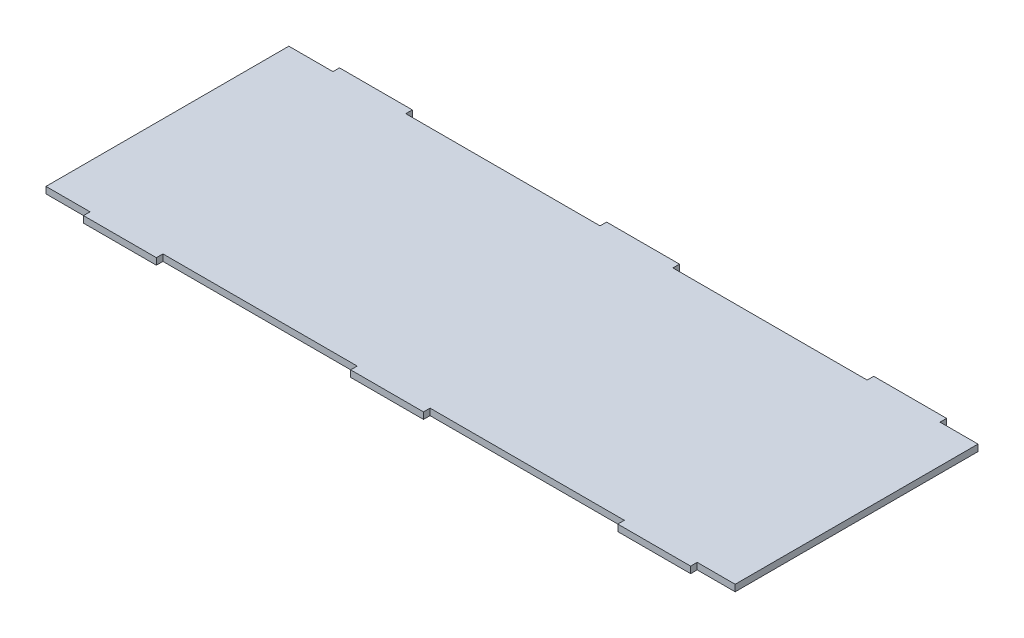
SolidWorks part; units mm, degrees
ref_plane "Front Plane" through (0, 0, 0) normal (0, 0, 1) x (1, 0, 0)
ref_plane "Top Plane" through (0, 0, 0) normal (0, 1, 0) x (1, 0, 0)
ref_plane "Right Plane" through (0, 0, 0) normal (1, 0, 0) x (0, 0, -1)
sketch "Sketch1" plane through (0, 0, 0) normal (0, 0, 1) x (1, 0, 0)
  line L1 (-300, 0) -> (0, 0)
  line L2 (-300, 0) -> (-300, 2.7)
  line L3 (-300, 2.7) -> (0, 2.7)
  line L4 (0, 0) -> (0, 2.7)
  point P4 (-257.3702, -10.115)
  point P5 (-6.4789, 13.0729)
  point P6 (-739.4101, 0)
  point P7 (0, 0)
  point P8 (0, 0)
  point P9 (-300, 0)
  dimension "D1" = 2.7
extrude "Boss-Extrude1" add sketch "Sketch1" along normal up to surface (100 mm away) contours L3 L4 L1 L2
sketch "Sketch3" plane through (0, 2.7, 0) normal (0, 1, 0) x (1, 0, 0)
  line L0 (-300, 0) -> (0, 0) construction
  line L1 (-50, 0) -> (-20, 0)
  line L2 (-50, 0) -> (-50, 2.7)
  line L3 (-50, 2.7) -> (-20, 2.7)
  line L4 (-20, 0) -> (-20, 2.7)
  line L5 (-160, 0) -> (-130, 0)
  line L6 (-160, 0) -> (-160, 2.7)
  line L7 (-160, 2.7) -> (-130, 2.7)
  line L8 (-130, 0) -> (-130, 2.7)
  line L9 (-270, 0) -> (-240, 0)
  line L10 (-270, 0) -> (-270, 2.7)
  line L11 (-270, 2.7) -> (-240, 2.7)
  line L12 (-240, 0) -> (-240, 2.7)
  line L13 (0, -50) -> (-300, -50) construction
  line L14 (0, -100) -> (0, 0) construction
  line L15 (-300, -100) -> (-300, 0) construction
  line L16 (-240, -100) -> (-240, -102.7)
  line L17 (-270, -102.7) -> (-240, -102.7)
  line L18 (-270, -100) -> (-270, -102.7)
  line L19 (-270, -100) -> (-240, -100)
  line L20 (-130, -100) -> (-130, -102.7)
  line L21 (-160, -102.7) -> (-130, -102.7)
  line L22 (-160, -100) -> (-160, -102.7)
  line L23 (-160, -100) -> (-130, -100)
  line L24 (-20, -100) -> (-20, -102.7)
  line L25 (-50, -102.7) -> (-20, -102.7)
  line L26 (-50, -100) -> (-50, -102.7)
  line L27 (-50, -100) -> (-20, -100)
  dimension "D1" = 50
  dimension "D2" = 30
  dimension "D4" = 2.7
  dimension "D3" = 3
extrude "Boss-Extrude2" add sketch "Sketch3" against normal up to surface (2.7 mm away) contours L21 L20 L23 L22 | L24 L25 L26 L27 | L16 L17 L18 L19 | L9 L12 L11 L10 | L5 L8 L7 L6 | L2 L1 L4 L3 up to face at (-150, 0, 50)
sketch "Sketch4" plane through (0, 0, 0) normal (0, 0, -1) x (-1, 0, 0)
  line L0 (300, 2.7) -> (288.1502, 2.7)
  line L1 (300, 2.7) -> (270, 2.7) construction
  line L3 (288.1502, 2.7) -> (288.1502, 0)
  line L5 (288.1502, 0) -> (300, 0)
  line L6 (300, 0) -> (300, 2.7)
  line L7 (270, 0) -> (304.7883, 0) construction
  line L8 (303.9345, -2.5614) -> (3.9345, 97.4386) construction
  point P5 (288.1502, 2.7)
  point P6 (283.3619, 2.7)
extrude "Cut-Extrude1" cut sketch "Sketch4" against normal through all
sketch "Sketch5" plane through (0, 2.7, 0) normal (0, 1, 0) x (1, 0, 0)
  line L1 (-4.3614, 0) -> (-4.3614, 2.7) construction
  line L2 (-4.3614, 0) -> (0, 0)
  line L3 (-4.3614, 0) -> (-4.3614, -100)
  line L4 (-4.3614, -100) -> (0, -100)
  line L5 (0, 0) -> (0, -100)
  line L6 (-4.3614, 0) -> (-4.3614, 2.7) construction
  point P0 (1.0865, 6.9467)
  point P4 (0.4269, 0)
  point P9 (-4.2793, 0)
extrude "Cut-Extrude2" cut sketch "Sketch5" against normal blind 2.7
